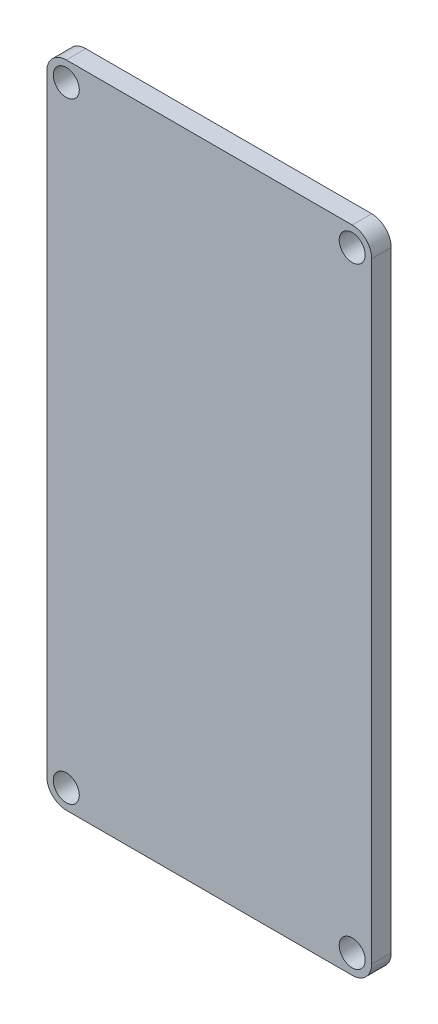
SolidWorks part; units mm, degrees
ref_plane "Front Plane" through (0, 0, 0) normal (0, 0, 1) x (1, 0, 0)
ref_plane "Top Plane" through (0, 0, 0) normal (0, 1, 0) x (1, 0, 0)
ref_plane "Right Plane" through (0, 0, 0) normal (1, 0, 0) x (0, 0, -1)
sketch "Sketch1" plane through (0, 0, 0) normal (0, 0, 1) x (1, 0, 0)
  line L1 (-22.007, -50.0002) -> (21.993, -50.0002)
  line L2 (-25.007, -47.0002) -> (-25.007, 46.9998)
  line L3 (-22.007, 49.9998) -> (21.993, 49.9998)
  line L4 (24.993, -47.0002) -> (24.993, 46.9998)
  line L5 (-25.007, -50.0002) -> (24.993, 49.9998) construction
  line L6 (-25.007, 49.9998) -> (24.993, -50.0002) construction
  line L7 (-22.007, -47.0002) -> (21.993, -47.0002)
  line L8 (-22.007, -47.0002) -> (-22.007, 46.9998)
  line L9 (-22.007, 46.9998) -> (21.993, 46.9998)
  line L10 (21.993, -47.0002) -> (21.993, 46.9998)
  line L11 (-22.007, -47.0002) -> (21.993, 46.9998) construction
  line L12 (-22.007, 46.9998) -> (21.993, -47.0002) construction
  arc A0 (-22.007, -50.0002) -> (-25.007, -47.0002) centre (-22.007, -47.0002) cw
  arc A1 (21.993, -50.0002) -> (24.993, -47.0002) centre (21.993, -47.0002) ccw
  arc A2 (21.993, 49.9998) -> (24.993, 46.9998) centre (21.993, 46.9998) cw
  arc A3 (-25.007, 46.9998) -> (-22.007, 49.9998) centre (-22.007, 46.9998) cw
  circle A4 centre (-22.007, 46.9998) radius 2
  circle A5 centre (21.993, 46.9998) radius 2
  circle A6 centre (21.993, -47.0002) radius 2
  circle A7 centre (-22.007, -47.0002) radius 2
  circle A8 centre (-22.007, 46.9998) radius 3
  circle A9 centre (21.993, 46.9998) radius 3
  circle A10 centre (21.993, -47.0002) radius 3
  circle A11 centre (-22.007, -47.0002) radius 3
  point P0 (-0.007, -0.0002)
  point P26 (-0.007, -0.0002)
  dimension "D3" = 3
  dimension "D4" = 4
  dimension "D1" = 100
  dimension "D2" = 50
extrude "Boss-Extrude1" add sketch "Sketch1" along normal blind 3 contours A9 L3 A8 L9 | L9 A8 A3 L8 A4 | A11 L7 A10 L10 A9 L9 A8 L8 | L8 A8 L9 A4 | A11 L8 A8 L2 | A2 A9 L9 A5 L10 | A10 L4 A9 L10 | L9 A9 L10 A5 | A1 A10 L10 A6 L7 | L10 A10 L7 A6 | A11 L1 A10 L7 | L8 A11 A0 L7 A7 | L7 A11 L8 A7
sketch "Sketch2" plane through (0, 0, 0) normal (0, 0, -1) x (-1, 0, 0)
  line L0 (12.5987, -31.1646) -> (12.5987, -29.7948)
  line L1 (-5.2662, 18.7244) -> (-4.8032, 18.2359)
  line L2 (12.5987, -29.7948) -> (20.007, -29.7948)
  line L3 (20.007, -29.7948) -> (20.007, -30.4596)
  line L4 (20.007, -30.4596) -> (13.3585, -30.4596)
  line L5 (13.3585, -30.4596) -> (13.3585, -31.5994)
  line L6 (13.3585, -31.5994) -> (12.5987, -31.1646)
  line L7 (14.8782, -11.6729) -> (14.8782, -12.3377)
  line L8 (17.2705, -9.1812) -> (19.2472, -11.0347)
  line L9 (19.2472, -11.0347) -> (19.2472, -7.5888)
  line L10 (19.2472, -7.5888) -> (20.007, -7.5888)
  line L11 (20.007, -7.5888) -> (20.007, -12.6227)
  line L12 (20.007, -12.6227) -> (16.941, -9.7496)
  line L13 (14.3083, 8.4436) -> (14.3083, 7.7787)
  line L14 (18.0125, 7.4938) -> (18.0125, 8.1587)
  line L15 (16.3029, 9.5833) -> (15.543, 9.5833)
  line L16 (12.4087, 31.6543) -> (12.4087, 31.7893)
  line L17 (12.4087, 31.7893) -> (17.5376, 31.7893)
  line L18 (17.5376, 31.7893) -> (17.5376, 32.6442)
  line L19 (17.5376, 32.6442) -> (18.2974, 32.6442)
  line L20 (18.2974, 32.6442) -> (18.2974, 31.7893)
  line L21 (18.2974, 31.7893) -> (20.007, 31.7893)
  line L22 (20.007, 31.7893) -> (20.007, 31.1245)
  line L23 (20.007, 31.1245) -> (18.2974, 31.1245)
  line L24 (18.2974, 31.1245) -> (18.2974, 27.6103)
  line L25 (18.2974, 27.6103) -> (12.4087, 31.6543)
  line L26 (17.5376, 31.1245) -> (14.3232, 31.1245)
  line L27 (14.3232, 31.1245) -> (17.5376, 28.9177)
  line L28 (17.5376, 28.9177) -> (17.5376, 31.1245)
  line L72 (-2.4423, 18.5615) -> (-2.4423, 16.4449)
  line L73 (-2.4423, 16.4449) -> (-3.0936, 16.4449)
  line L74 (-3.0936, 16.4449) -> (-3.0936, 19.1314)
  line L75 (-6.35, 1.0583) -> (-6.35, 1.6282)
  line L76 (-6.35, 1.6282) -> (-0.6513, 1.6282)
  line L77 (-0.6513, 1.6282) -> (-0.6513, 4.0705)
  line L78 (-0.6513, 4.0705) -> (0, 4.0705)
  line L79 (0, 4.0705) -> (0, 1.0583)
  line L80 (0, 1.0583) -> (-6.35, 1.0583)
  line L81 (-6.35, -2.8494) -> (0, 0.0814)
  line L82 (0, 0.0814) -> (0, -0.5381)
  line L83 (0, -0.5381) -> (-2.0353, -1.4768)
  line L84 (-2.0353, -1.4768) -> (-2.0353, -4.3554)
  line L85 (-2.0353, -4.3554) -> (0, -5.3197)
  line L86 (0, -5.3197) -> (0, -5.9429)
  line L87 (0, -5.9429) -> (-6.35, -2.9308)
  line L88 (-6.35, -2.9308) -> (-6.35, -2.8494)
  line L89 (-5.111, -2.8964) -> (-2.6865, -4.0451)
  line L90 (-2.6865, -4.0451) -> (-2.6865, -1.777)
  line L91 (-2.6865, -1.777) -> (-5.111, -2.8964)
  line L92 (0, -11.9673) -> (-6.35, -11.9673)
  line L93 (-6.35, -11.9673) -> (-6.35, -11.8477)
  line L94 (-6.35, -11.8477) -> (-1.3522, -7.6526)
  line L95 (-1.3522, -7.6526) -> (-6.35, -7.6526)
  line L96 (-6.35, -7.6526) -> (-6.35, -7.0827)
  line L97 (-6.35, -7.0827) -> (0, -7.0827)
  line L98 (0, -7.0827) -> (0, -7.2124)
  line L99 (0, -7.2124) -> (-4.9864, -11.3974)
  line L100 (-4.9864, -11.3974) -> (0, -11.3974)
  line L101 (0, -11.3974) -> (0, -11.9673)
  line L102 (-6.35, -15.875) -> (0, -12.9442)
  line L103 (0, -12.9442) -> (0, -13.5637)
  line L104 (0, -13.5637) -> (-2.0353, -14.5025)
  line L105 (-2.0353, -14.5025) -> (-2.0353, -17.3811)
  line L106 (-2.0353, -17.3811) -> (0, -18.3453)
  line L107 (0, -18.3453) -> (0, -18.9686)
  line L108 (0, -18.9686) -> (-6.35, -15.9564)
  line L109 (-6.35, -15.9564) -> (-6.35, -15.875)
  line L110 (-5.111, -15.9221) -> (-2.6865, -17.0707)
  line L111 (-2.6865, -17.0707) -> (-2.6865, -14.8027)
  line L112 (-2.6865, -14.8027) -> (-5.111, -15.9221)
  spline S0 degree 3 poles (14.8782, -12.3377) (14.7048, -12.3335) (14.4502, -12.3057) (14.1228, -12.2279) (13.8944, -12.1474) (13.6772, -12.0472) (13.4719, -11.9272) (13.2793, -11.7849) (13.1012, -11.6236) (12.9378, -11.4484) (12.7967, -11.2594) (12.6775, -11.0608) (12.5778, -10.8531) (12.5031, -10.6341) (12.4277, -10.3253) (12.4084, -10.0842) (12.4087, -9.9217) knots 0 0 0 0 0.135103 0.198979 0.261904 0.323495 0.385195 0.446969 0.509765 0.572251 0.633405 0.693251 0.752583 0.812579 0.873275 1 1 1 1
  spline S1 degree 3 poles (12.4087, -9.9217) (12.4082, -9.7621) (12.4286, -9.5273) (12.4962, -9.2257) (12.5695, -9.0167) (12.6616, -8.8186) (12.7761, -8.6341) (12.9076, -8.4586) (13.0627, -8.3007) (13.2282, -8.1557) (13.4049, -8.0306) (13.5877, -7.923) (13.7779, -7.8349) (13.9762, -7.7681) (14.252, -7.7011) (14.4671, -7.6856) (14.6111, -7.6838) knots 0 0 0 0 0.136525 0.200801 0.263983 0.325711 0.387271 0.449493 0.512955 0.576266 0.637575 0.697901 0.757558 0.816588 0.876646 1 1 1 1
  spline S2 degree 3 poles (14.6111, -7.6838) (14.8157, -7.6829) (15.1211, -7.7226) (15.5107, -7.8502) (15.7452, -7.965) (15.9345, -8.079) (16.0901, -8.1824) (16.2569, -8.3044) (16.437, -8.4439) (16.6273, -8.6038) (16.9124, -8.8449) (17.1232, -9.045) (17.2705, -9.1812) knots 0 0 0 0 0.195649 0.292388 0.391297 0.444816 0.503919 0.570035 0.642593 0.721961 0.807944 1 1 1 1
  spline S3 degree 3 poles (16.941, -9.7496) (16.8011, -9.6149) (16.5982, -9.4228) (16.333, -9.1845) (16.1582, -9.0321) (15.996, -8.9012) (15.8516, -8.7851) (15.7188, -8.692) (15.5648, -8.591) (15.3768, -8.4933) (15.0715, -8.3809) (14.8301, -8.3485) (14.6704, -8.3486) knots 0 0 0 0 0.212829 0.306101 0.390647 0.466924 0.534481 0.593587 0.644557 0.7362 0.825024 1 1 1 1
  spline S4 degree 3 poles (14.6704, -8.3486) (14.5708, -8.3481) (14.4232, -8.3634) (14.2333, -8.4114) (14.0971, -8.4621) (13.9671, -8.529) (13.843, -8.6104) (13.723, -8.7044) (13.6105, -8.8131) (13.5074, -8.9325) (13.4161, -9.0586) (13.3398, -9.1921) (13.2773, -9.3323) (13.2283, -9.4788) (13.182, -9.6863) (13.169, -9.847) (13.1686, -9.9558) knots 0 0 0 0 0.122122 0.180988 0.239933 0.299906 0.359989 0.421776 0.486576 0.551535 0.615018 0.677259 0.73973 0.80305 0.866495 1 1 1 1
  spline S5 degree 3 poles (13.1686, -9.9558) (13.1687, -10.0697) (13.1826, -10.2375) (13.2273, -10.4545) (13.2793, -10.6057) (13.3409, -10.7512) (13.419, -10.8878) (13.5098, -11.018) (13.6151, -11.1395) (13.7335, -11.2505) (13.8639, -11.3493) (14.0054, -11.4351) (14.1575, -11.5101) (14.3217, -11.5709) (14.5613, -11.6347) (14.7493, -11.6637) (14.8782, -11.6729) knots 0 0 0 0 0.12653 0.186744 0.245898 0.304053 0.362196 0.420655 0.480331 0.540663 0.600744 0.661982 0.72448 0.789067 0.856333 1 1 1 1
  spline S6 degree 3 poles (14.3083, 7.7787) (14.1614, 7.8098) (13.9507, 7.8762) (13.6826, 7.9855) (13.5003, 8.0815) (13.3293, 8.1863) (13.1733, 8.3064) (13.0285, 8.4361) (12.9, 8.5797) (12.7837, 8.7303) (12.6844, 8.8899) (12.5991, 9.0555) (12.5288, 9.2281) (12.4759, 9.4083) (12.4237, 9.6594) (12.4078, 9.8533) (12.4087, 9.984) knots 0 0 0 0 0.141977 0.208985 0.273957 0.336889 0.398745 0.460116 0.520825 0.580994 0.640152 0.698622 0.757271 0.816427 0.876254 1 1 1 1
  spline S7 degree 3 poles (12.4087, 9.984) (12.4077, 10.1753) (12.4411, 10.4605) (12.5537, 10.824) (12.6689, 11.082) (12.8111, 11.3217) (12.9804, 11.5349) (13.1734, 11.7188) (13.3866, 11.8731) (13.6145, 11.9938) (13.9253, 12.1125) (14.1712, 12.1472) (14.3335, 12.1478) knots 0 0 0 0 0.17854 0.266093 0.354631 0.441886 0.525747 0.608114 0.690197 0.770821 0.848326 1 1 1 1
  spline S8 degree 3 poles (14.3335, 12.1478) (14.4865, 12.1475) (14.7143, 12.1243) (14.9998, 12.0306) (15.1988, 11.9353) (15.3844, 11.8118) (15.621, 11.6076) (15.7693, 11.4187) (15.8577, 11.2826) knots 0 0 0 0 0.250608 0.37063 0.490072 0.610375 0.734313 1 1 1 1
  spline S9 degree 3 poles (15.8577, 11.2826) (15.9265, 11.4421) (16.107, 11.7383) (16.3519, 11.9841) (16.4899, 12.0854) knots 0 0 0 0 0.503896 1 1 1 1
  spline S10 degree 3 poles (16.4899, 12.0854) (16.5843, 12.1596) (16.7369, 12.2522) (16.9485, 12.3582) (17.1118, 12.42) (17.2792, 12.4677) (17.5097, 12.5138) (17.687, 12.527) (17.8062, 12.5277) knots 0 0 0 0 0.254173 0.378112 0.501712 0.623986 0.747096 1 1 1 1
  spline S11 degree 3 poles (17.8062, 12.5277) (18.0134, 12.5293) (18.3248, 12.4838) (18.7216, 12.3434) (19.0077, 12.1946) (19.275, 12.0121) (19.516, 11.7975) (19.7199, 11.5476) (19.8923, 11.2714) (20.0288, 10.971) (20.1624, 10.5384) (20.1965, 10.1954) (20.197, 9.9647) knots 0 0 0 0 0.158908 0.239599 0.322582 0.406 0.487843 0.569676 0.65302 0.737412 0.822558 1 1 1 1
  spline S12 degree 3 poles (20.197, 9.9647) (20.1951, 9.8092) (20.1835, 9.5781) (20.121, 9.2822) (20.0633, 9.0727) (19.9834, 8.875) (19.8881, 8.6865) (19.7751, 8.5079) (19.644, 8.3402) (19.4974, 8.1837) (19.3326, 8.0423) (19.1529, 7.9145) (18.9565, 7.8011) (18.744, 7.7016) (18.431, 7.5873) (18.1836, 7.5239) (18.0125, 7.4938) knots 0 0 0 0 0.128956 0.190367 0.249965 0.308569 0.366415 0.424556 0.483181 0.542251 0.601744 0.662508 0.7245 0.789139 0.856354 1 1 1 1
  spline S13 degree 3 poles (18.0125, 8.1587) (18.1234, 8.1919) (18.2857, 8.2427) (18.4865, 8.3324) (18.6207, 8.4024) (18.7439, 8.4761) (18.8866, 8.5833) (18.9829, 8.6724) (19.0365, 8.7389) knots 0 0 0 0 0.291316 0.425966 0.55216 0.671527 0.786122 1 1 1 1
  spline S14 degree 3 poles (19.0365, 8.7389) (19.1023, 8.8201) (19.191, 8.951) (19.2838, 9.1406) (19.3407, 9.2916) (19.3833, 9.4513) (19.4254, 9.6794) (19.4382, 9.8565) (19.4372, 9.9766) knots 0 0 0 0 0.236156 0.35563 0.476249 0.600164 0.728633 1 1 1 1
  spline S15 degree 3 poles (19.4372, 9.9766) (19.4379, 10.1122) (19.4225, 10.3111) (19.3757, 10.5675) (19.323, 10.744) (19.2578, 10.9111) (19.176, 11.0664) (19.08, 11.212) (18.971, 11.346) (18.8515, 11.4666) (18.7266, 11.5727) (18.5968, 11.6629) (18.4612, 11.7357) (18.3205, 11.7931) (18.1246, 11.846) (17.9725, 11.8649) (17.87, 11.8628) knots 0 0 0 0 0.148752 0.218403 0.28576 0.350598 0.414964 0.478069 0.541761 0.60435 0.664075 0.721464 0.777587 0.832644 0.887844 1 1 1 1
  spline S16 degree 3 poles (17.87, 11.8628) (17.7325, 11.8621) (17.5245, 11.8311) (17.2653, 11.7221) (17.0798, 11.61) (16.91, 11.4701) (16.7574, 11.3092) (16.6316, 11.1228) (16.5446, 10.9513) (16.4853, 10.7994) (16.4457, 10.6694) (16.4123, 10.5239) (16.3811, 10.3645) (16.3546, 10.1902) (16.324, 9.9288) (16.31, 9.7245) (16.3029, 9.5833) knots 0 0 0 0 0.13348 0.201027 0.271634 0.342905 0.413859 0.485996 0.560246 0.599899 0.644068 0.691904 0.744697 0.801499 0.862863 1 1 1 1
  spline S17 degree 3 poles (15.543, 9.5833) (15.5437, 9.7627) (15.5238, 10.0275) (15.4499, 10.3673) (15.3727, 10.6013) (15.2817, 10.8142) (15.1765, 10.9997) (15.0575, 11.1528) (14.9269, 11.2752) (14.7876, 11.3681) (14.5934, 11.4575) (14.4351, 11.4822) (14.3306, 11.4829) knots 0 0 0 0 0.215729 0.318104 0.417658 0.511742 0.59626 0.673405 0.744145 0.810662 0.874049 1 1 1 1
  spline S18 degree 3 poles (14.3306, 11.4829) (14.2535, 11.4848) (14.1392, 11.4692) (13.9927, 11.4258) (13.888, 11.3793) (13.7879, 11.3189) (13.6911, 11.2461) (13.5989, 11.1588) (13.5109, 11.061) (13.4309, 10.9527) (13.3608, 10.8364) (13.3014, 10.7127) (13.2522, 10.5822) (13.2153, 10.4444) (13.1791, 10.2483) (13.1691, 10.0961) (13.1686, 9.9929) knots 0 0 0 0 0.109958 0.163912 0.218089 0.273309 0.330914 0.390994 0.454641 0.518898 0.583342 0.648543 0.715053 0.782519 0.852334 1 1 1 1
  spline S19 degree 3 poles (13.1686, 9.9929) (13.1682, 9.8284) (13.1982, 9.5858) (13.3081, 9.2855) (13.404, 9.1167) (13.4987, 8.9921) (13.5814, 8.903) (13.6734, 8.8156) (13.7802, 8.7354) (13.8946, 8.6545) (14.0701, 8.5531) (14.2101, 8.4854) (14.3083, 8.4436) knots 0 0 0 0 0.239685 0.351816 0.463766 0.520818 0.579448 0.640604 0.705298 0.773634 0.844669 1 1 1 1
  spline S20 degree 3 poles (-4.8032, 18.2359) (-4.9719, 18.0656) (-5.2, 17.7912) (-5.4478, 17.3912) (-5.5967, 17.0833) (-5.7132, 16.7717) (-5.8253, 16.3651) (-5.8622, 16.0557) (-5.8615, 15.8521) knots 0 0 0 0 0.269021 0.398733 0.527306 0.652311 0.771699 1 1 1 1
  spline S21 degree 3 poles (-5.8615, 15.8521) (-5.8631, 15.7291) (-5.8497, 15.5459) (-5.8126, 15.3045) (-5.7729, 15.1261) (-5.7224, 14.9496) (-5.6593, 14.7757) (-5.5857, 14.6039) (-5.5007, 14.436) (-5.4073, 14.2731) (-5.3038, 14.1194) (-5.1935, 13.9736) (-5.0736, 13.8388) (-4.9454, 13.7138) (-4.8111, 13.5965) (-4.668, 13.489) (-4.5168, 13.3932) (-4.361, 13.3067) (-4.202, 13.232) (-4.041, 13.167) (-3.8771, 13.1175) (-3.7118, 13.0756) (-3.4878, 13.0365) (-3.3169, 13.0271) (-3.203, 13.0256) knots 0 0 0 0 0.085568 0.127714 0.170062 0.212779 0.255472 0.298866 0.342848 0.386513 0.429516 0.471868 0.51371 0.555061 0.596513 0.637859 0.67956 0.721068 0.76189 0.801925 0.841812 0.881065 0.920636 1 1 1 1
  spline S22 degree 3 poles (-3.203, 13.0256) (-3.0862, 13.027) (-2.9106, 13.0362) (-2.6811, 13.0799) (-2.5115, 13.123) (-2.3439, 13.178) (-2.1785, 13.2454) (-2.0153, 13.3258) (-1.8559, 13.4187) (-1.7008, 13.5212) (-1.5535, 13.634) (-1.4156, 13.7571) (-1.2853, 13.8885) (-1.1632, 14.0292) (-1.0509, 14.1807) (-0.9467, 14.3407) (-0.8516, 14.5094) (-0.7667, 14.6851) (-0.6911, 14.8651) (-0.629, 15.0503) (-0.5783, 15.2394) (-0.5368, 15.4324) (-0.5006, 15.6979) (-0.4866, 15.8996) (-0.4885, 16.0353) knots 0 0 0 0 0.077886 0.116658 0.155425 0.194361 0.234007 0.274295 0.315417 0.356772 0.398061 0.438867 0.479803 0.521246 0.562815 0.605269 0.648388 0.691709 0.735134 0.778356 0.821651 0.865516 0.909726 1 1 1 1
  spline S23 degree 3 poles (-0.4885, 16.0353) (-0.4886, 16.1969) (-0.505, 16.4358) (-0.561, 16.7452) (-0.6212, 16.9633) (-0.6976, 17.1721) (-0.792, 17.3708) (-0.9034, 17.56) (-1.0297, 17.7387) (-1.1704, 17.9029) (-1.3209, 18.0523) (-1.4831, 18.1818) (-1.6545, 18.2953) (-1.837, 18.389) (-2.096, 18.493) (-2.3021, 18.5405) (-2.4423, 18.5615) knots 0 0 0 0 0.138708 0.204939 0.269469 0.332671 0.395498 0.457967 0.520867 0.583068 0.643278 0.702549 0.760882 0.819471 0.878256 1 1 1 1
  spline S24 degree 3 poles (-3.0936, 19.1314) (-2.8562, 19.1299) (-2.5071, 19.1051) (-2.0609, 19.0111) (-1.7525, 18.9174) (-1.4635, 18.7961) (-1.1935, 18.6485) (-0.9442, 18.4722) (-0.7137, 18.2735) (-0.5081, 18.0505) (-0.3274, 17.8093) (-0.1752, 17.5494) (-0.0513, 17.271) (0.0452, 16.9752) (0.139, 16.5474) (0.1619, 16.2129) (0.1628, 15.9857) knots 0 0 0 0 0.139493 0.204635 0.267406 0.328446 0.388397 0.447734 0.507392 0.566768 0.625478 0.684067 0.743248 0.804033 0.866499 1 1 1 1
  spline S25 degree 3 poles (0.1628, 15.9857) (0.1625, 15.8443) (0.1532, 15.6351) (0.123, 15.3607) (0.0894, 15.1635) (0.0481, 14.9713) (-0.0046, 14.7851) (-0.0657, 14.6042) (-0.1352, 14.4284) (-0.2157, 14.2592) (-0.3052, 14.0958) (-0.4031, 13.9375) (-0.5113, 13.7852) (-0.6288, 13.6381) (-0.7994, 13.449) (-0.9401, 13.3178) (-1.038, 13.2343) knots 0 0 0 0 0.136557 0.202094 0.266464 0.329769 0.391879 0.453271 0.514115 0.57439 0.634142 0.693923 0.754152 0.81447 0.875661 1 1 1 1
  spline S26 degree 3 poles (-1.038, 13.2343) (-1.1887, 13.108) (-1.427, 12.9371) (-1.7697, 12.7559) (-2.0338, 12.6463) (-2.3072, 12.5609) (-2.6869, 12.478) (-2.9806, 12.4574) (-3.1775, 12.4558) knots 0 0 0 0 0.253668 0.376738 0.499344 0.621999 0.745699 1 1 1 1
  spline S27 degree 3 poles (-3.1775, 12.4558) (-3.326, 12.454) (-3.5472, 12.4702) (-3.8375, 12.5154) (-4.0498, 12.5644) (-4.2582, 12.6262) (-4.4628, 12.7034) (-4.6636, 12.7933) (-4.8593, 12.8978) (-5.0473, 13.0141) (-5.2268, 13.1403) (-5.3947, 13.2777) (-5.5515, 13.4264) (-5.6996, 13.5836) (-5.8357, 13.7524) (-5.9621, 13.9305) (-6.0763, 14.1191) (-6.179, 14.3153) (-6.2689, 14.5186) (-6.3433, 14.7289) (-6.4064, 14.9448) (-6.453, 15.1678) (-6.499, 15.4761) (-6.5145, 15.7121) (-6.5128, 15.8712) knots 0 0 0 0 0.083545 0.124644 0.165305 0.206173 0.246974 0.288333 0.32999 0.371802 0.412742 0.453464 0.493833 0.534375 0.574947 0.615887 0.657246 0.699003 0.740483 0.782323 0.824565 0.86704 0.910499 1 1 1 1
  spline S28 degree 3 poles (-6.5128, 15.8712) (-6.5124, 16.0015) (-6.5032, 16.196) (-6.4723, 16.4523) (-6.4411, 16.6406) (-6.3985, 16.8255) (-6.3476, 17.0076) (-6.2883, 17.1871) (-6.2175, 17.3635) (-6.1372, 17.538) (-6.0469, 17.7115) (-5.9448, 17.8834) (-5.8309, 18.054) (-5.707, 18.2245) (-5.5212, 18.4514) (-5.3726, 18.6175) (-5.2662, 18.7244) knots 0 0 0 0 0.122179 0.182216 0.241864 0.30096 0.359969 0.419033 0.478069 0.537993 0.59896 0.661321 0.725248 0.79122 0.858746 1 1 1 1
  spline S29 degree 3 poles (-6.5128, 8.1003) (-6.5121, 8.3311) (-6.4855, 8.6733) (-6.3837, 9.1127) (-6.2781, 9.4233) (-6.1411, 9.7184) (-5.9746, 9.999) (-5.7778, 10.2641) (-5.5533, 10.5121) (-5.3076, 10.7383) (-5.0445, 10.9367) (-4.7673, 11.1042) (-4.4761, 11.2413) (-4.1716, 11.3487) (-3.7398, 11.4496) (-3.4044, 11.4793) (-3.1775, 11.4788) knots 0 0 0 0 0.130742 0.193348 0.254998 0.316119 0.377264 0.4394 0.502805 0.566356 0.628251 0.689107 0.749358 0.81018 0.871617 1 1 1 1
  spline S30 degree 3 poles (-3.1775, 11.4788) (-2.9524, 11.4793) (-2.619, 11.4496) (-2.1901, 11.3484) (-1.886, 11.2426) (-1.5954, 11.1054) (-1.3181, 10.9377) (-1.0542, 10.7396) (-0.8068, 10.5144) (-0.5804, 10.2681) (-0.3807, 10.006) (-0.2132, 9.7289) (-0.0746, 9.4396) (0.0307, 9.1359) (0.1349, 8.7089) (0.1627, 8.3757) (0.1628, 8.1512) knots 0 0 0 0 0.128584 0.190343 0.251408 0.312206 0.373614 0.436264 0.500407 0.564535 0.627137 0.688338 0.74924 0.810076 0.871656 1 1 1 1
  spline S31 degree 3 poles (0.1628, 8.1512) (0.1633, 7.9244) (0.1335, 7.5885) (0.0326, 7.1565) (-0.0734, 6.8508) (-0.2107, 6.5589) (-0.3779, 6.2805) (-0.5764, 6.0165) (-0.8017, 5.7691) (-1.047, 5.5428) (-1.3097, 5.3454) (-1.5849, 5.1781) (-1.8732, 5.0414) (-2.1732, 4.9332) (-2.5966, 4.8329) (-2.9252, 4.8025) (-3.147, 4.8032) knots 0 0 0 0 0.129747 0.192072 0.253459 0.31457 0.37628 0.439026 0.503267 0.567493 0.629705 0.691 0.751452 0.812004 0.87315 1 1 1 1
  spline S32 degree 3 poles (-3.147, 4.8032) (-3.2972, 4.8015) (-3.5209, 4.8175) (-3.8149, 4.863) (-4.03, 4.9112) (-4.2404, 4.9744) (-4.4475, 5.0489) (-4.6492, 5.1398) (-4.8465, 5.2427) (-5.0363, 5.3574) (-5.2157, 5.4842) (-5.3862, 5.6185) (-5.5434, 5.7658) (-5.6919, 5.9211) (-5.8293, 6.087) (-5.957, 6.2626) (-6.0721, 6.4484) (-6.1762, 6.64) (-6.2655, 6.8376) (-6.3421, 7.0383) (-6.4042, 7.2433) (-6.4532, 7.4518) (-6.4984, 7.737) (-6.5146, 7.9544) (-6.5128, 8.1003) knots 0 0 0 0 0.085873 0.12812 0.170152 0.211918 0.253753 0.296006 0.338443 0.381015 0.42282 0.464089 0.505126 0.545975 0.586985 0.628339 0.670084 0.711992 0.753039 0.794049 0.834886 0.875498 0.916547 1 1 1 1
  spline S33 degree 3 poles (-5.8615, 8.1283) (-5.8632, 8.0083) (-5.8496, 7.8293) (-5.8127, 7.5938) (-5.7731, 7.4204) (-5.7218, 7.2493) (-5.6599, 7.0804) (-5.5851, 6.9142) (-5.501, 6.751) (-5.4055, 6.5946) (-5.3041, 6.4446) (-5.193, 6.3048) (-5.0746, 6.1733) (-4.9479, 6.0506) (-4.8137, 5.9366) (-4.6715, 5.8314) (-4.5218, 5.7363) (-4.3654, 5.6517) (-4.2055, 5.5759) (-4.0399, 5.5131) (-3.87, 5.4633) (-3.6962, 5.4212) (-3.4561, 5.3852) (-3.273, 5.3711) (-3.1496, 5.3731) knots 0 0 0 0 0.083632 0.124965 0.166222 0.207584 0.249508 0.291612 0.334606 0.37747 0.419392 0.460873 0.501919 0.542707 0.583836 0.624654 0.666009 0.707437 0.748588 0.789403 0.830765 0.87209 0.914006 1 1 1 1
  spline S34 degree 3 poles (-3.1496, 5.3731) (-2.9691, 5.3725) (-2.7021, 5.3976) (-2.3584, 5.4815) (-2.1156, 5.5709) (-1.8832, 5.6851) (-1.6622, 5.8244) (-1.4527, 5.9901) (-1.2562, 6.1781) (-1.0769, 6.3837) (-0.9193, 6.602) (-0.7867, 6.8311) (-0.6758, 7.0698) (-0.5924, 7.3201) (-0.5114, 7.6715) (-0.4869, 7.9441) (-0.4885, 8.1283) knots 0 0 0 0 0.126894 0.187739 0.24842 0.308586 0.36958 0.431822 0.496172 0.560657 0.623491 0.685245 0.746643 0.808335 0.870491 1 1 1 1
  spline S35 degree 3 poles (-0.4885, 8.1283) (-0.4879, 8.2528) (-0.4987, 8.4388) (-0.5359, 8.6828) (-0.5758, 8.861) (-0.6251, 9.0358) (-0.6863, 9.2067) (-0.7596, 9.3736) (-0.8413, 9.5373) (-0.9342, 9.6941) (-1.0342, 9.8433) (-1.1434, 9.9828) (-1.2602, 10.1142) (-1.3865, 10.2361) (-1.5199, 10.3497) (-1.6624, 10.4531) (-1.8115, 10.5479) (-1.9667, 10.6335) (-2.1271, 10.7071) (-2.2919, 10.7699) (-2.4611, 10.8206) (-2.6345, 10.8603) (-2.8735, 10.8974) (-3.0558, 10.9106) (-3.1788, 10.909) knots 0 0 0 0 0.086549 0.129194 0.171459 0.213444 0.255398 0.297507 0.340084 0.382496 0.424107 0.464849 0.505555 0.546202 0.586772 0.627275 0.668486 0.709511 0.750395 0.791069 0.832005 0.873119 0.9146 1 1 1 1
  spline S36 degree 3 poles (-3.1788, 10.909) (-3.3009, 10.9106) (-3.4821, 10.8974) (-3.7193, 10.8602) (-3.8911, 10.8208) (-4.0581, 10.7699) (-4.2204, 10.7072) (-4.3785, 10.6332) (-4.532, 10.5482) (-4.6793, 10.4528) (-4.82, 10.3485) (-4.9517, 10.2335) (-5.0775, 10.1112) (-5.1948, 9.9785) (-5.3033, 9.8354) (-5.4078, 9.6856) (-5.5002, 9.5256) (-5.586, 9.361) (-5.6592, 9.192) (-5.7221, 9.021) (-5.7733, 8.8472) (-5.8125, 8.6708) (-5.8496, 8.4315) (-5.8632, 8.25) (-5.8615, 8.1283) knots 0 0 0 0 0.085123 0.126463 0.167439 0.207959 0.248229 0.288726 0.329643 0.370507 0.411095 0.451782 0.492365 0.533442 0.575216 0.617557 0.660784 0.704049 0.746973 0.789181 0.831118 0.873248 0.915173 1 1 1 1
  point P6 (20.007, 0)
  point P8 (0, 0)
extrude "Boss-Extrude2" add sketch "Sketch2" along normal blind 1
